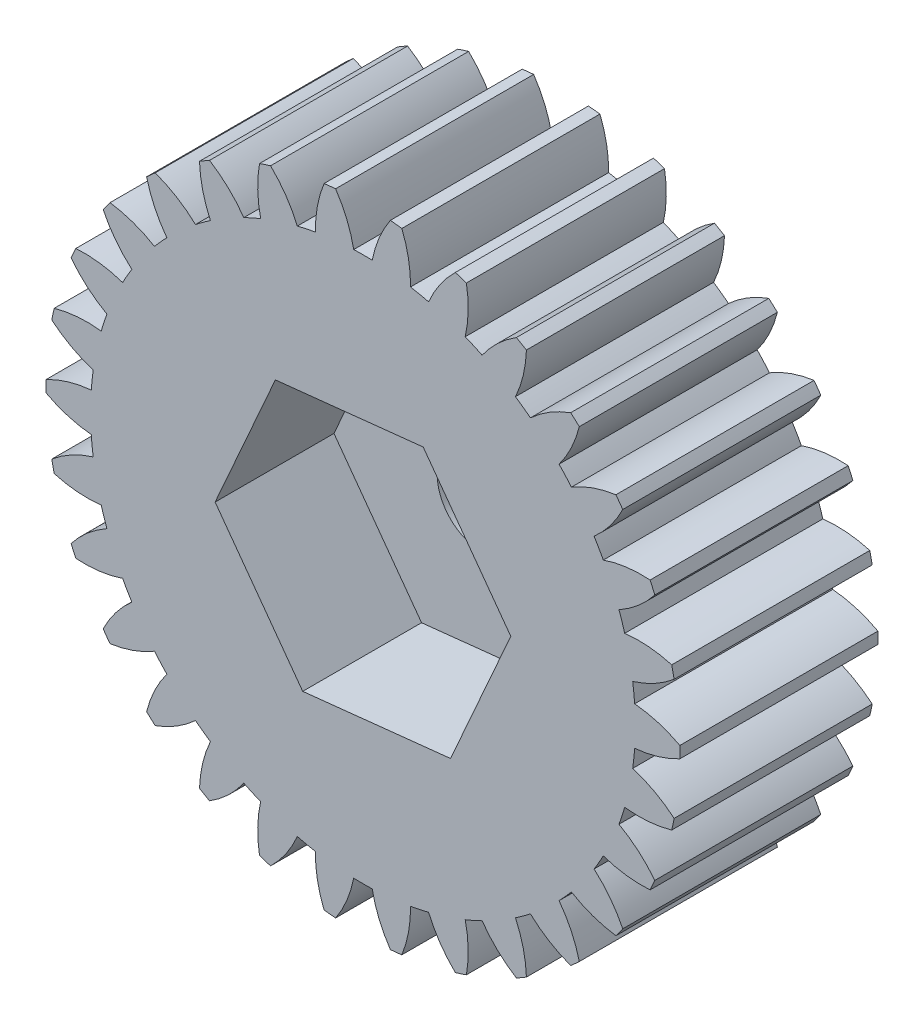
SolidWorks part; units mm, degrees
ref_plane "Front Plane" through (0, 0, 0) normal (0, 0, 1) x (1, 0, 0)
ref_plane "Top Plane" through (0, 0, 0) normal (0, 1, 0) x (1, 0, 0)
ref_plane "Right Plane" through (0, 0, 0) normal (1, 0, 0) x (0, 0, -1)
sketch "Sketch1" plane through (0, 0, 0) normal (0, 0, 1) x (1, 0, 0)
  arc A0 (13.7146, 1.8356) -> (15.9973, 2.5155) centre (13.1775, 7.8115) ccw
  arc A1 (15.9973, 2.5155) -> (15.9973, 3.1008) centre (0, 2.8081) ccw
  arc A2 (15.9973, 3.1008) -> (13.7146, 3.7806) centre (13.1775, -2.1953) ccw
  arc A3 (13.7146, 3.7806) -> (13.6171, 4.7083) centre (0, 2.8081) ccw
  arc A4 (13.6171, 4.7083) -> (15.7086, 5.8479) centre (11.8492, 10.4419) ccw
  arc A5 (15.7086, 5.8479) -> (15.5869, 6.4204) centre (0, 2.8081) ccw
  arc A6 (15.5869, 6.4204) -> (13.2127, 6.6108) centre (13.9298, 0.6538) ccw
  arc A7 (13.2127, 6.6108) -> (12.9244, 7.4979) centre (0, 2.8081) ccw
  arc A8 (12.9244, 7.4979) -> (14.7333, 9.0475) centre (10.0031, 12.7387) ccw
  arc A9 (14.7333, 9.0475) -> (14.4952, 9.5822) centre (0, 2.8081) ccw
  arc A10 (14.4952, 9.5822) -> (12.1333, 9.2747) centre (14.0733, 3.597) ccw
  arc A11 (12.1333, 9.2747) -> (11.6669, 10.0826) centre (0, 2.8081) ccw
  arc A12 (11.6669, 10.0826) -> (13.1141, 11.9743) centre (7.7199, 14.6015) ccw
  arc A13 (13.1141, 11.9743) -> (12.7701, 12.4479) centre (0, 2.8081) ccw
  arc A14 (12.7701, 12.4479) -> (10.5237, 11.6561) centre (13.6017, 6.5058) ccw
  arc A15 (10.5237, 11.6561) -> (9.8995, 12.3493) centre (0, 2.8081) ccw
  arc A16 (9.8995, 12.3493) -> (10.9218, 14.5006) centre (5.0992, 15.9488) ccw
  arc A17 (10.9218, 14.5006) -> (10.4868, 14.8923) centre (0, 2.8081) ccw
  arc A18 (10.4868, 14.8923) -> (8.4541, 13.6507) centre (12.5357, 9.2529) ccw
  arc A19 (8.4541, 13.6507) -> (7.6995, 14.199) centre (0, 2.8081) ccw
  arc A20 (7.6995, 14.199) -> (8.2521, 16.5159) centre (2.2556, 16.7218) ccw
  arc A21 (8.2521, 16.5159) -> (7.7452, 16.8085) centre (0, 2.8081) ccw
  arc A22 (7.7452, 16.8085) -> (6.0151, 15.1715) centre (10.9218, 11.7184) ccw
  arc A23 (6.0151, 15.1715) -> (5.1629, 15.5509) centre (0, 2.8081) ccw
  arc A24 (5.1629, 15.5509) -> (5.2218, 17.932) centre (-0.6865, 16.8868) ccw
  arc A25 (5.2218, 17.932) -> (4.6651, 18.1129) centre (0, 2.8081) ccw
  arc A26 (4.6651, 18.1129) -> (3.3131, 16.1519) centre (8.8306, 13.7945) ccw
  arc A27 (3.3131, 16.1519) -> (2.4007, 16.3459) centre (0, 2.8081) ccw
  arc A28 (2.4007, 16.3459) -> (1.9632, 18.6872) centre (-3.5986, 16.4364) ccw
  arc A29 (1.9632, 18.6872) -> (1.3811, 18.7484) centre (0, 2.8081) ccw
  arc A30 (1.3811, 18.7484) -> (0.4664, 16.5492) centre (6.3534, 15.3904) ccw
  arc A31 (0.4664, 16.5492) -> (-0.4664, 16.5492) centre (0, 2.8081) ccw
  arc A32 (-0.4664, 16.5492) -> (-1.3811, 18.7484) centre (-6.3534, 15.3904) ccw
  arc A33 (-1.3811, 18.7484) -> (-1.9632, 18.6872) centre (0, 2.8081) ccw
  arc A34 (-1.9632, 18.6872) -> (-2.4007, 16.3459) centre (3.5986, 16.4364) ccw
  arc A35 (-2.4007, 16.3459) -> (-3.3131, 16.1519) centre (0, 2.8081) ccw
  arc A36 (-3.3131, 16.1519) -> (-4.6651, 18.1129) centre (-8.8306, 13.7945) ccw
  arc A37 (-4.6651, 18.1129) -> (-5.2218, 17.932) centre (0, 2.8081) ccw
  arc A38 (-5.2218, 17.932) -> (-5.1629, 15.5509) centre (0.6865, 16.8868) ccw
  arc A39 (-5.1629, 15.5509) -> (-6.0151, 15.1715) centre (0, 2.8081) ccw
  arc A40 (-6.0151, 15.1715) -> (-7.7452, 16.8085) centre (-10.9218, 11.7184) ccw
  arc A41 (-7.7452, 16.8085) -> (-8.2521, 16.5159) centre (0, 2.8081) ccw
  arc A42 (-8.2521, 16.5159) -> (-7.6995, 14.199) centre (-2.2556, 16.7218) ccw
  arc A43 (-7.6995, 14.199) -> (-8.4541, 13.6507) centre (0, 2.8081) ccw
  arc A44 (-8.4541, 13.6507) -> (-10.4868, 14.8923) centre (-12.5357, 9.2529) ccw
  arc A45 (-10.4868, 14.8923) -> (-10.9218, 14.5006) centre (0, 2.8081) ccw
  arc A46 (-10.9218, 14.5006) -> (-9.8995, 12.3493) centre (-5.0992, 15.9488) ccw
  arc A47 (-9.8995, 12.3493) -> (-10.5237, 11.6561) centre (0, 2.8081) ccw
  arc A48 (-10.5237, 11.6561) -> (-12.7701, 12.4479) centre (-13.6017, 6.5058) ccw
  arc A49 (-12.7701, 12.4479) -> (-13.1141, 11.9743) centre (0, 2.8081) ccw
  arc A50 (-13.1141, 11.9743) -> (-11.6669, 10.0826) centre (-7.7199, 14.6015) ccw
  arc A51 (-11.6669, 10.0826) -> (-12.1333, 9.2747) centre (0, 2.8081) ccw
  arc A52 (-12.1333, 9.2747) -> (-14.4952, 9.5822) centre (-14.0733, 3.597) ccw
  arc A53 (-14.4952, 9.5822) -> (-14.7333, 9.0475) centre (0, 2.8081) ccw
  arc A54 (-14.7333, 9.0475) -> (-12.9244, 7.4979) centre (-10.0031, 12.7387) ccw
  arc A55 (-12.9244, 7.4979) -> (-13.2127, 6.6108) centre (0, 2.8081) ccw
  arc A56 (-13.2127, 6.6108) -> (-15.5869, 6.4204) centre (-13.9298, 0.6538) ccw
  arc A57 (-15.5869, 6.4204) -> (-15.7086, 5.8479) centre (0, 2.8081) ccw
  arc A58 (-15.7086, 5.8479) -> (-13.6171, 4.7083) centre (-11.8492, 10.4419) ccw
  arc A59 (-13.6171, 4.7083) -> (-13.7146, 3.7806) centre (0, 2.8081) ccw
  arc A60 (-13.7146, 3.7806) -> (-15.9973, 3.1008) centre (-13.1775, -2.1953) ccw
  arc A61 (-15.9973, 3.1008) -> (-15.9973, 2.5155) centre (0, 2.8081) ccw
  arc A62 (-15.9973, 2.5155) -> (-13.7146, 1.8356) centre (-13.1775, 7.8115) ccw
  arc A63 (-13.7146, 1.8356) -> (-13.6171, 0.9079) centre (0, 2.8081) ccw
  arc A64 (-13.6171, 0.9079) -> (-15.7086, -0.2317) centre (-11.8492, -4.8257) ccw
  arc A65 (-15.7086, -0.2317) -> (-15.5869, -0.8042) centre (0, 2.8081) ccw
  arc A66 (-15.5869, -0.8042) -> (-13.2127, -0.9945) centre (-13.9298, 4.9624) ccw
  arc A67 (-13.2127, -0.9945) -> (-12.9244, -1.8817) centre (0, 2.8081) ccw
  arc A68 (-12.9244, -1.8817) -> (-14.7333, -3.4312) centre (-10.0031, -7.1225) ccw
  arc A69 (-14.7333, -3.4312) -> (-14.4952, -3.9659) centre (0, 2.8081) ccw
  arc A70 (-14.4952, -3.9659) -> (-12.1333, -3.6585) centre (-14.0733, 2.0192) ccw
  arc A71 (-12.1333, -3.6585) -> (-11.6669, -4.4664) centre (0, 2.8081) ccw
  arc A72 (-11.6669, -4.4664) -> (-13.1141, -6.3581) centre (-7.7199, -8.9853) ccw
  arc A73 (-13.1141, -6.3581) -> (-12.7701, -6.8316) centre (0, 2.8081) ccw
  arc A74 (-12.7701, -6.8316) -> (-10.5237, -6.0399) centre (-13.6017, -0.8896) ccw
  arc A75 (-10.5237, -6.0399) -> (-9.8995, -6.7331) centre (0, 2.8081) ccw
  arc A76 (-9.8995, -6.7331) -> (-10.9218, -8.8844) centre (-5.0992, -10.3326) ccw
  arc A77 (-10.9218, -8.8844) -> (-10.4868, -9.276) centre (0, 2.8081) ccw
  arc A78 (-10.4868, -9.276) -> (-8.4541, -8.0345) centre (-12.5357, -3.6367) ccw
  arc A79 (-8.4541, -8.0345) -> (-7.6995, -8.5828) centre (0, 2.8081) ccw
  arc A80 (-7.6995, -8.5828) -> (-8.2521, -10.8997) centre (-2.2556, -11.1056) ccw
  arc A81 (-8.2521, -10.8997) -> (-7.7452, -11.1923) centre (0, 2.8081) ccw
  arc A82 (-7.7452, -11.1923) -> (-6.0151, -9.5553) centre (-10.9218, -6.1022) ccw
  arc A83 (-6.0151, -9.5553) -> (-5.1629, -9.9347) centre (0, 2.8081) ccw
  arc A84 (-5.1629, -9.9347) -> (-5.2218, -12.3158) centre (0.6865, -11.2706) ccw
  arc A85 (-5.2218, -12.3158) -> (-4.6651, -12.4967) centre (0, 2.8081) ccw
  arc A86 (-4.6651, -12.4967) -> (-3.3131, -10.5357) centre (-8.8306, -8.1783) ccw
  arc A87 (-3.3131, -10.5357) -> (-2.4007, -10.7297) centre (0, 2.8081) ccw
  arc A88 (-2.4007, -10.7297) -> (-1.9632, -13.071) centre (3.5986, -10.8202) ccw
  arc A89 (-1.9632, -13.071) -> (-1.3811, -13.1322) centre (0, 2.8081) ccw
  arc A90 (-1.3811, -13.1322) -> (-0.4664, -10.933) centre (-6.3534, -9.7742) ccw
  arc A91 (-0.4664, -10.933) -> (0.4664, -10.933) centre (0, 2.8081) ccw
  arc A92 (0.4664, -10.933) -> (1.3811, -13.1322) centre (6.3534, -9.7742) ccw
  arc A93 (1.3811, -13.1322) -> (1.9632, -13.071) centre (0, 2.8081) ccw
  arc A94 (1.9632, -13.071) -> (2.4007, -10.7297) centre (-3.5986, -10.8202) ccw
  arc A95 (2.4007, -10.7297) -> (3.3131, -10.5357) centre (0, 2.8081) ccw
  arc A96 (3.3131, -10.5357) -> (4.6651, -12.4967) centre (8.8306, -8.1783) ccw
  arc A97 (4.6651, -12.4967) -> (5.2218, -12.3158) centre (0, 2.8081) ccw
  arc A98 (5.2218, -12.3158) -> (5.1629, -9.9347) centre (-0.6865, -11.2706) ccw
  arc A99 (5.1629, -9.9347) -> (6.0151, -9.5553) centre (0, 2.8081) ccw
  arc A100 (6.0151, -9.5553) -> (7.7452, -11.1923) centre (10.9218, -6.1022) ccw
  arc A101 (7.7452, -11.1923) -> (8.2521, -10.8997) centre (0, 2.8081) ccw
  arc A102 (8.2521, -10.8997) -> (7.6995, -8.5828) centre (2.2556, -11.1056) ccw
  arc A103 (7.6995, -8.5828) -> (8.4541, -8.0345) centre (0, 2.8081) ccw
  arc A104 (8.4541, -8.0345) -> (10.4868, -9.276) centre (12.5357, -3.6367) ccw
  arc A105 (10.4868, -9.276) -> (10.9218, -8.8844) centre (0, 2.8081) ccw
  arc A106 (10.9218, -8.8844) -> (9.8995, -6.7331) centre (5.0992, -10.3326) ccw
  arc A107 (9.8995, -6.7331) -> (10.5237, -6.0399) centre (0, 2.8081) ccw
  arc A108 (10.5237, -6.0399) -> (12.7701, -6.8316) centre (13.6017, -0.8896) ccw
  arc A109 (12.7701, -6.8316) -> (13.1141, -6.3581) centre (0, 2.8081) ccw
  arc A110 (13.1141, -6.3581) -> (11.6669, -4.4664) centre (7.7199, -8.9853) ccw
  arc A111 (11.6669, -4.4664) -> (12.1333, -3.6585) centre (0, 2.8081) ccw
  arc A112 (12.1333, -3.6585) -> (14.4952, -3.9659) centre (14.0733, 2.0192) ccw
  arc A113 (14.4952, -3.9659) -> (14.7333, -3.4312) centre (0, 2.8081) ccw
  arc A114 (14.7333, -3.4312) -> (12.9244, -1.8817) centre (10.0031, -7.1225) ccw
  arc A115 (12.9244, -1.8817) -> (13.2127, -0.9945) centre (0, 2.8081) ccw
  arc A116 (13.2127, -0.9945) -> (15.5869, -0.8042) centre (13.9298, 4.9624) ccw
  arc A117 (15.5869, -0.8042) -> (15.7086, -0.2317) centre (0, 2.8081) ccw
  arc A118 (15.7086, -0.2317) -> (13.6171, 0.9079) centre (11.8492, -4.8257) ccw
  arc A119 (13.6171, 0.9079) -> (13.7146, 1.8356) centre (0, 2.8081) ccw
extrude "Boss-Extrude1" add sketch "Sketch1" along normal blind 10
sketch "Sketch2" plane through (0, 0, 0) normal (0, 0, -1) x (-1, 0, 0)
  circle A0 centre (0, 2.8081) radius 2.25
  dimension "D1" = 4.5
extrude "Cut-Extrude1" cut sketch "Sketch2" against normal blind 10
sketch "Sketch3" plane through (0, 0, 10) normal (0, 0, 1) x (1, 0, 0)
  line L0 (3.0414, 9.6698) -> (7.4631, 3.6051)
  line L1 (7.4631, 3.6051) -> (4.4218, -3.2567)
  line L2 (4.4218, -3.2567) -> (-3.0414, -4.0536)
  line L3 (-3.0414, -4.0536) -> (-7.4631, 2.0111)
  line L4 (-7.4631, 2.0111) -> (-4.4218, 8.8729)
  line L5 (-4.4218, 8.8729) -> (3.0414, 9.6698)
  point P14 (0, 0)
  point P15 (0, 0)
  point P16 (0, 0)
extrude "Cut-Extrude2" cut sketch "Sketch3" against normal blind 6
